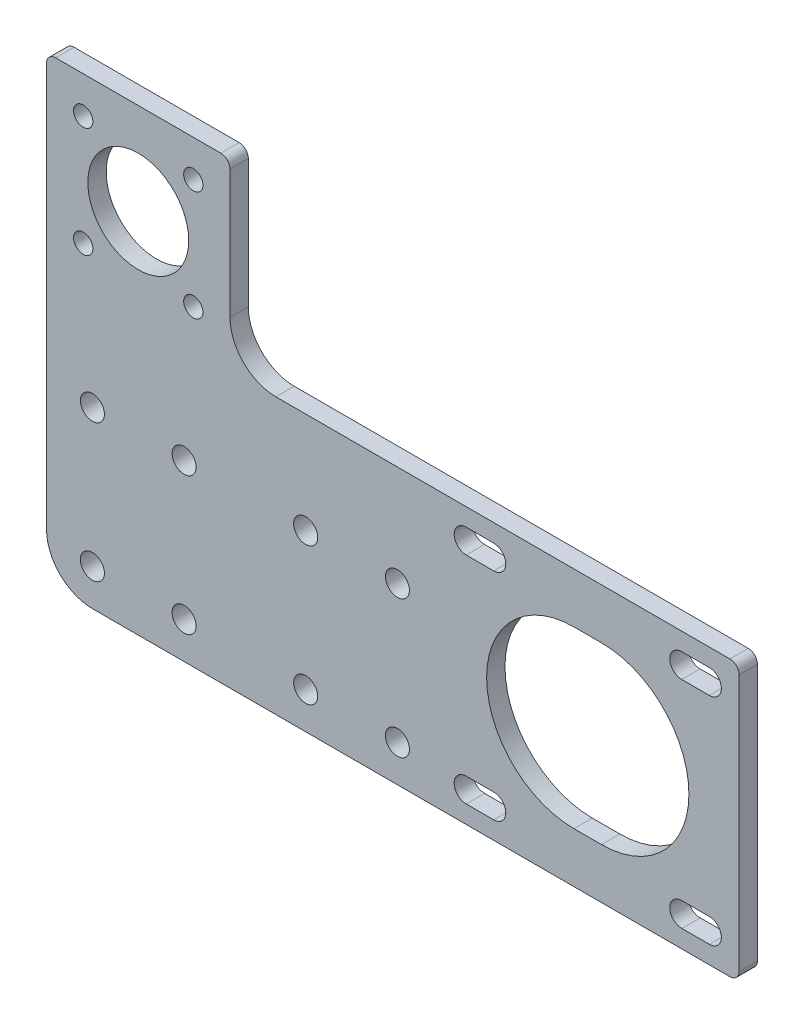
SolidWorks part; units mm, degrees
ref_plane "前视基准面" through (0, 0, 0) normal (0, 0, 1) x (1, 0, 0)
ref_plane "上视基准面" through (0, 0, 0) normal (0, 1, 0) x (1, 0, 0)
ref_plane "右视基准面" through (0, 0, 0) normal (1, 0, 0) x (0, 0, -1)
sketch "Model" plane through (0, 0, 0) normal (0, 0, 1) x (1, 0, 0)
  line L64 (-98, 28.5924) -> (-98, 66.8065) construction
  line L65 (-81.1355, 50) -> (-115.327, 50) construction
  line L66 (-37.3904, 0) -> (29.987, 0) construction
  line L67 (0, 28.5924) -> (0, -25.7118) construction
  line L68 (23.5, 13.0051) -> (23.5, 34.1234) construction
  line L69 (9.8744, 23.5) -> (36.0208, 23.5) construction
  line L70 (-20.5, -20.875) -> (-26.5, -20.875)
  line L71 (-26.5, -26.125) -> (-20.5, -26.125)
  line L72 (20.5, 20.875) -> (26.5, 20.875)
  line L73 (26.5, 26.125) -> (20.5, 26.125)
  line L74 (-3, -19.05) -> (3, -19.05)
  line L75 (3, 19.05) -> (-3, 19.05)
  line L76 (-80, 70) -> (-116, 70)
  line L77 (-78, 40) -> (-78, 68)
  line L78 (31, 30) -> (-68, 30)
  line L79 (33, -28) -> (33, 28)
  line L80 (-108, -30) -> (31, -30)
  line L81 (-118, 68) -> (-118, -20)
  line L82 (-26.5, 20.875) -> (-20.5, 20.875)
  line L83 (-20.5, 26.125) -> (-26.5, 26.125)
  line L84 (26.5, -20.875) -> (20.5, -20.875)
  line L85 (20.5, -26.125) -> (26.5, -26.125)
  arc A0 (-26.5, -20.875) -> (-26.5, -26.125) centre (-26.5, -23.5) ccw
  arc A1 (-20.5, -26.125) -> (-20.5, -20.875) centre (-20.5, -23.5) ccw
  arc A2 (26.5, 20.875) -> (26.5, 26.125) centre (26.5, 23.5) ccw
  arc A3 (20.5, 26.125) -> (20.5, 20.875) centre (20.5, 23.5) ccw
  arc A4 (3, -19.05) -> (3, 19.05) centre (3, 0) ccw
  arc A5 (-3, 19.05) -> (-3, -19.05) centre (-3, 0) ccw
  arc A6 (-116, 70) -> (-118, 68) centre (-116, 68) ccw
  arc A7 (-78, 68) -> (-80, 70) centre (-80, 68) ccw
  arc A8 (-78, 40) -> (-68, 30) centre (-68, 40) ccw
  arc A9 (33, 28) -> (31, 30) centre (31, 28) ccw
  arc A10 (31, -30) -> (33, -28) centre (31, -28) ccw
  arc A11 (-118, -20) -> (-108, -30) centre (-108, -20) ccw
  circle A12 centre (-98, 50) radius 11
  arc A13 (-20.5, 20.875) -> (-20.5, 26.125) centre (-20.5, 23.5) ccw
  arc A14 (-26.5, 26.125) -> (-26.5, 20.875) centre (-26.5, 23.5) ccw
  arc A15 (20.5, -20.875) -> (20.5, -26.125) centre (20.5, -23.5) ccw
  arc A16 (26.5, -26.125) -> (26.5, -20.875) centre (26.5, -23.5) ccw
  circle A17 centre (-110, 62) radius 2.1
  circle A18 centre (-86, 62) radius 2.1
  circle A19 centre (-110, 38) radius 2.1
  circle A20 centre (-86, 38) radius 2.1
  circle A21 centre (-61.5, 8) radius 2.625
  circle A22 centre (-41.5, 8) radius 2.625
  circle A23 centre (-41.5, -22) radius 2.625
  circle A24 centre (-61.5, -22) radius 2.625
  circle A25 centre (-108, 8) radius 2.625
  circle A26 centre (-88, 8) radius 2.625
  circle A27 centre (-108, -22) radius 2.625
  circle A28 centre (-88, -22) radius 2.625
extrude "凸台-拉伸1" add sketch "Model" along normal blind 4
